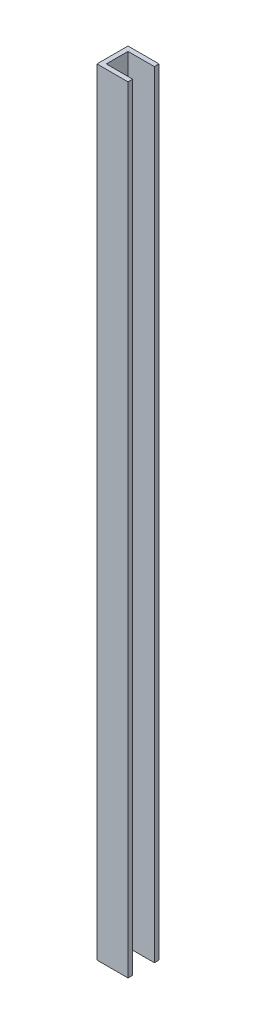
SolidWorks part; units mm, degrees
ref_plane "Front Plane" through (0, 0, 0) normal (0, 0, 1) x (1, 0, 0)
ref_plane "Top Plane" through (0, 0, 0) normal (0, 1, 0) x (1, 0, 0)
ref_plane "Right Plane" through (0, 0, 0) normal (1, 0, 0) x (0, 0, -1)
sketch "Sketch2" plane through (0, 0, 0) normal (0, 1, 0) x (1, 0, 0)
  line L1 (-5, -5) -> (5, -5)
  line L2 (-5, -5) -> (-5, 5)
  line L3 (-5, 5) -> (5, 5)
  line L4 (5, -5) -> (5, 5)
  line L5 (-5, -5) -> (5, 5) construction
  line L6 (-5, 5) -> (5, -5) construction
  line L7 (5, 3.5) -> (-3.5, 3.5)
  line L8 (5, 3.5) -> (5, -3.5)
  line L9 (5, -3.5) -> (-3.5, -3.5)
  line L10 (-3.5, 3.5) -> (-3.5, -3.5)
  point P0 (0, 0)
  dimension "D1" = 1.5
  dimension "D2" = 1.5
  dimension "D3" = 10
extrude "Boss-Extrude1" add sketch "Sketch2" along normal mid plane 250 contours L10 L7 L4 L3 L2 L1 L9
